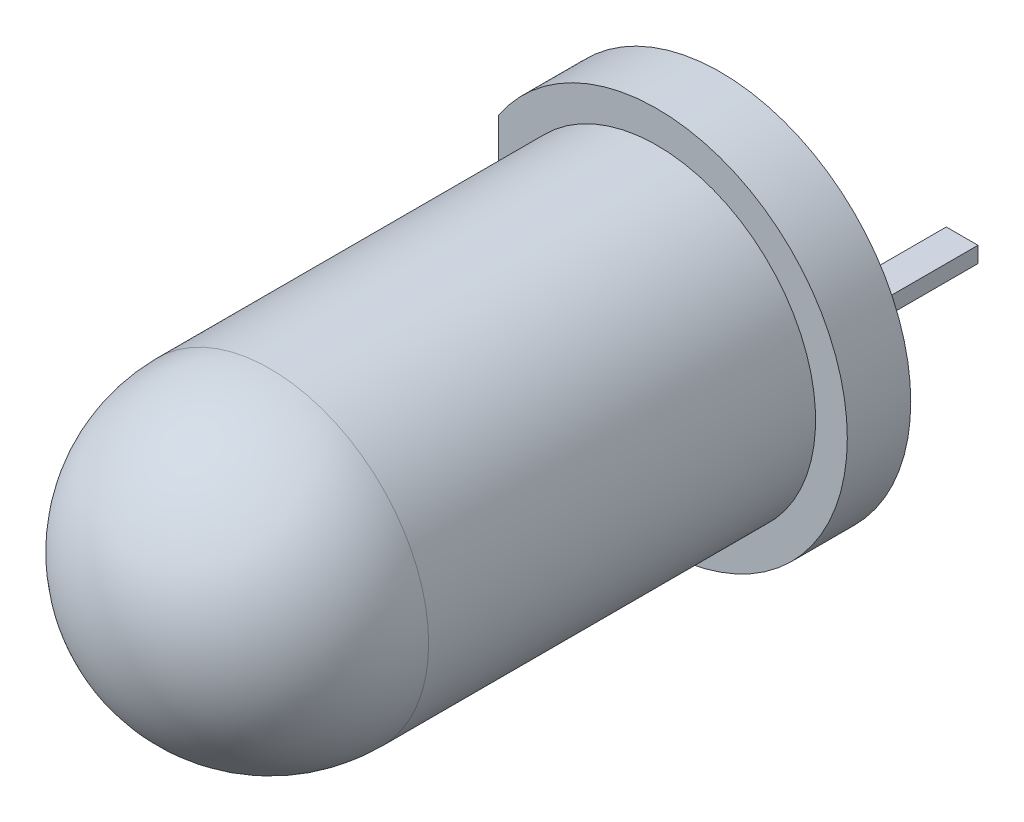
SolidWorks part; units mm, degrees
ref_plane "Plano frontal" through (0, 0, 0) normal (0, 0, 1) x (1, 0, 0)
ref_plane "Plano superior" through (0, 0, 0) normal (0, 1, 0) x (1, 0, 0)
ref_plane "Plano direito" through (0, 0, 0) normal (1, 0, 0) x (0, 0, -1)
sketch "Esboço1" plane through (0, 0, 0) normal (0, 0, 1) x (1, 0, 0)
  circle A0 centre (0, 0) radius 2.5
  dimension "D1" = 5
extrude "Ressalto-extrusão1" add sketch "Esboço1" along normal blind 8.6
sketch "Esboço2" plane through (0, 0, 0) normal (0, 0, -1) x (-1, 0, 0)
  line L0 (2.5, 0) -> (2.5, 1.6583)
  line L1 (2.5, 0) -> (2.5, -1.6583)
  arc A0 (2.5, 1.6583) -> (2.5, -1.6583) centre (0, 0) ccw
  circle A1 centre (0, 0) radius 2.5 construction
  dimension "D1" = 6
extrude "Ressalto-extrusão2" add sketch "Esboço2" along normal blind 1
fillet "Filete1" radius 2.5 1 edges at (2.5, 0, 8.6)
sketch "Esboço3" plane through (0, 0, -1) normal (0, 0, -1) x (-1, 0, 0)
  line L0 (-3, 0) -> (3, 0) construction
  line L1 (0, 0) -> (0, 1.2856) construction
  line L2 (0, 1.2856) -> (-1.27, 1.2856) construction
  line L3 (-1.27, 1.2856) -> (-1.27, 0) construction
  line L4 (0, 1.2856) -> (1.27, 1.2856) construction
  line L5 (1.27, 1.2856) -> (1.27, 0) construction
  line L7 (1.02, 0.125) -> (1.52, 0.125)
  line L8 (1.02, 0.125) -> (1.02, -0.125)
  line L9 (1.02, -0.125) -> (1.52, -0.125)
  line L10 (1.52, 0.125) -> (1.52, -0.125)
  line L11 (1.02, 0.125) -> (1.52, -0.125) construction
  line L12 (1.02, -0.125) -> (1.52, 0.125) construction
  line L13 (-1.02, 0.125) -> (-1.52, 0.125)
  line L14 (-1.02, 0.125) -> (-1.02, -0.125)
  line L15 (-1.02, -0.125) -> (-1.52, -0.125)
  line L16 (-1.52, 0.125) -> (-1.52, -0.125)
  line L17 (-1.02, 0.125) -> (-1.52, -0.125) construction
  line L18 (-1.02, -0.125) -> (-1.52, 0.125) construction
  circle A0 centre (0, 0) radius 3 construction
  dimension "D1" = 2.54
  dimension "D2" = 1.27
  dimension "D3" = 0.5
  dimension "D4" = 0.5
  dimension "D5" = 0.25
  dimension "D6" = 0.25
extrude "Ressalto-extrusão3" add sketch "Esboço3" along normal blind 2.54
sketch "Esboço4" plane through (0, 0, -3.54) normal (0, 0, -1) x (-1, 0, 0)
  line L1 (0.8217, 0.3828) -> (1.7572, 0.3828)
  line L2 (0.8217, 0.3828) -> (0.8217, -0.3709)
  line L3 (0.8217, -0.3709) -> (1.7572, -0.3709)
  line L4 (1.7572, 0.3828) -> (1.7572, -0.3709)
extrude "Corte-extrusão1" cut sketch "Esboço4" against normal blind 1
